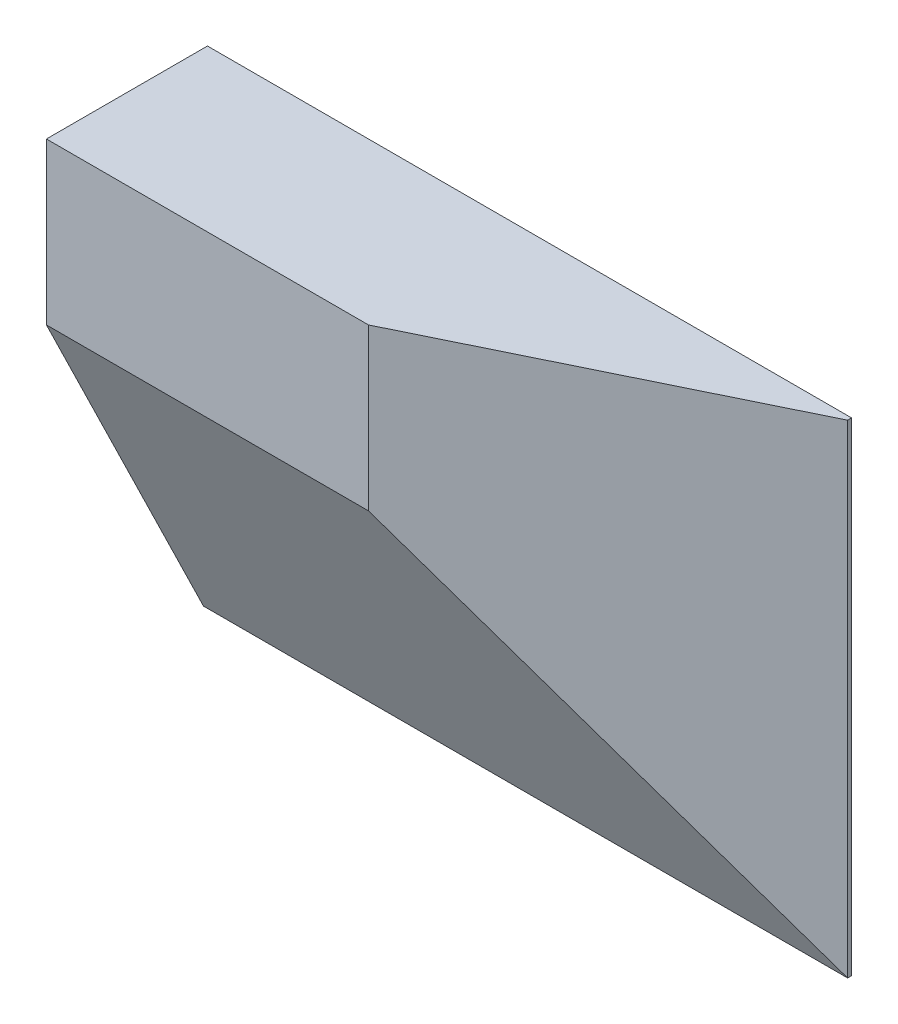
SolidWorks part; units mm, degrees
ref_plane "Front Plane" through (0, 0, 0) normal (0, 0, 1) x (1, 0, 0)
ref_plane "Top Plane" through (0, 0, 0) normal (0, 1, 0) x (1, 0, 0)
ref_plane "Right Plane" through (0, 0, 0) normal (1, 0, 0) x (0, 0, -1)
sketch "Sketch1" plane through (0, 0, 0) normal (1, 0, 0) x (0, 0, -1)
  line L1 (5, 15) -> (-5, 15)
  line L2 (5, 15) -> (5, -15)
  line L3 (5, -15) -> (-5, -15)
  line L4 (-5, 15) -> (-5, -15)
  line L5 (5, 15) -> (-5, -15) construction
  line L6 (5, -15) -> (-5, 15) construction
  point P0 (0, 0)
  dimension "D1" = 10
  dimension "D2" = 30
extrude "Boss-Extrude1" add sketch "Sketch1" along normal blind 40
chamfer "Chamfer1" distance 20 angle 26 1 edges at (40, 0, 5)
chamfer "Chamfer2" distance 20 angle 26 1 edges at (10, -15, 5)
